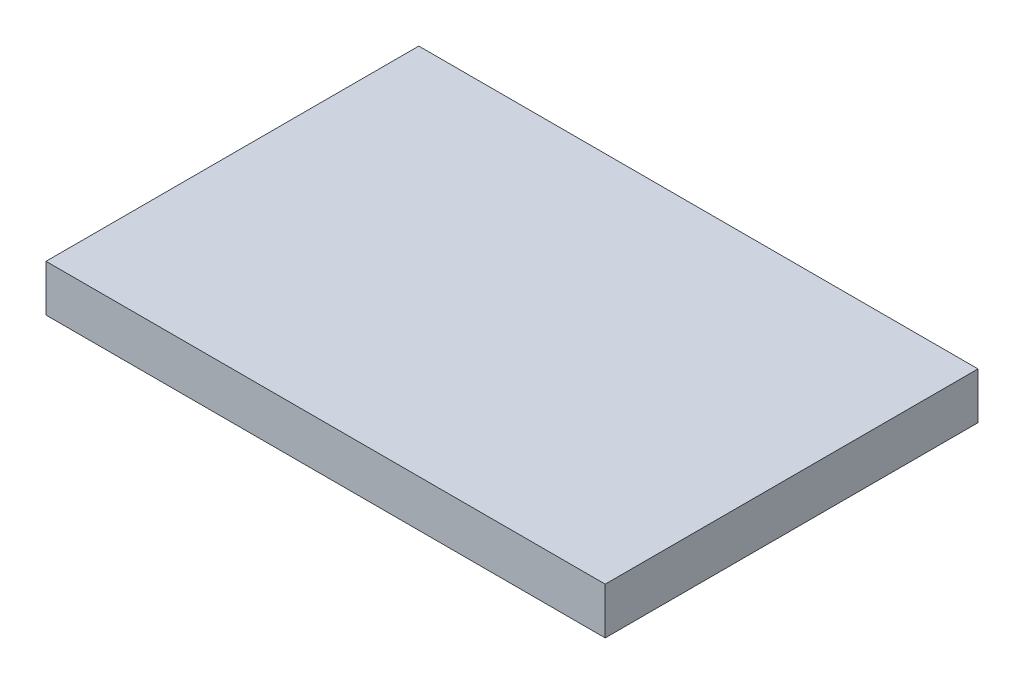
SolidWorks part; units mm, degrees
ref_plane "Front Plane" through (0, 0, 0) normal (0, 0, 1) x (1, 0, 0)
ref_plane "Top Plane" through (0, 0, 0) normal (0, 1, 0) x (1, 0, 0)
ref_plane "Right Plane" through (0, 0, 0) normal (1, 0, 0) x (0, 0, -1)
sketch "Sketch1" plane through (0, 0, 0) normal (0, 1, 0) x (1, 0, 0)
  line L1 (0, 0) -> (12, 0)
  line L2 (0, 0) -> (0, 8)
  line L3 (0, 8) -> (12, 8)
  line L4 (12, 0) -> (12, 8)
  dimension "D1" = 8
  dimension "D2" = 12
extrude "Boss-Extrude1" add sketch "Sketch1" along normal blind 1
